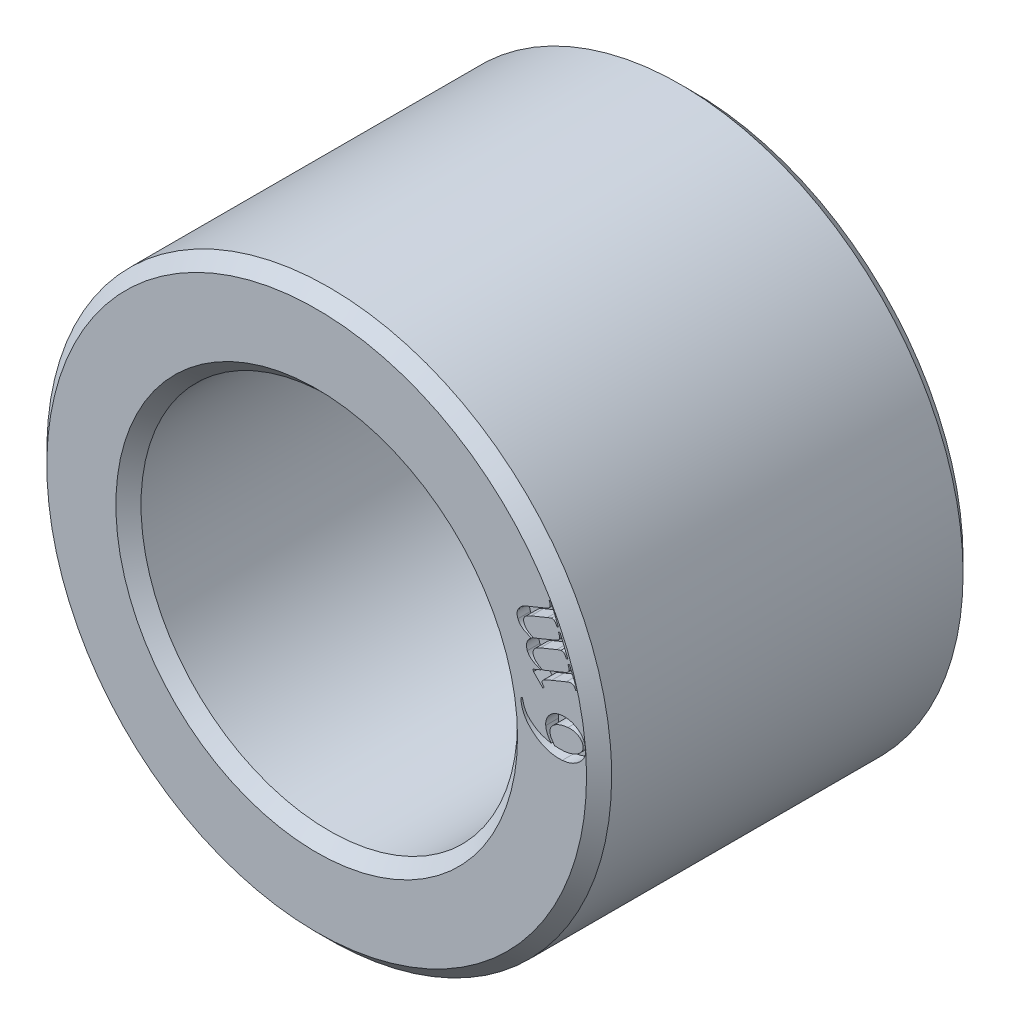
SolidWorks part; units mm, degrees
ref_plane "Plan de face" through (0, 0, 0) normal (0, 0, 1) x (1, 0, 0)
ref_plane "Plan de dessus" through (0, 0, 0) normal (0, 1, 0) x (1, 0, 0)
ref_plane "Plan de droite" through (0, 0, 0) normal (1, 0, 0) x (0, 0, -1)
sketch "Esquisse1" plane through (0, 0, 0) normal (0, 0, 1) x (1, 0, 0)
  circle A0 centre (0, 0) radius 3
  circle A1 centre (0, 0) radius 4.5
  dimension "D1" = 1.5
  dimension "D2" = 6
extrude "Boss.-Extru.1" add sketch "Esquisse1" along normal blind 6
chamfer "Chanfrein1" distance 0.2 angle 45 4 edges at (4.5, 0, 0) (3, 0, 0) (4.5, 0, 6) (3, 0, 6)
sketch "Esquisse2" plane through (0, 0, 6) normal (0, 0, 1) x (1, 0, 0)
  text T0 "6 m" font "Times New Roman" height in points 4
extrude "Enlèv. mat.-Extru.1" cut sketch "Esquisse2" against normal blind 0.2
